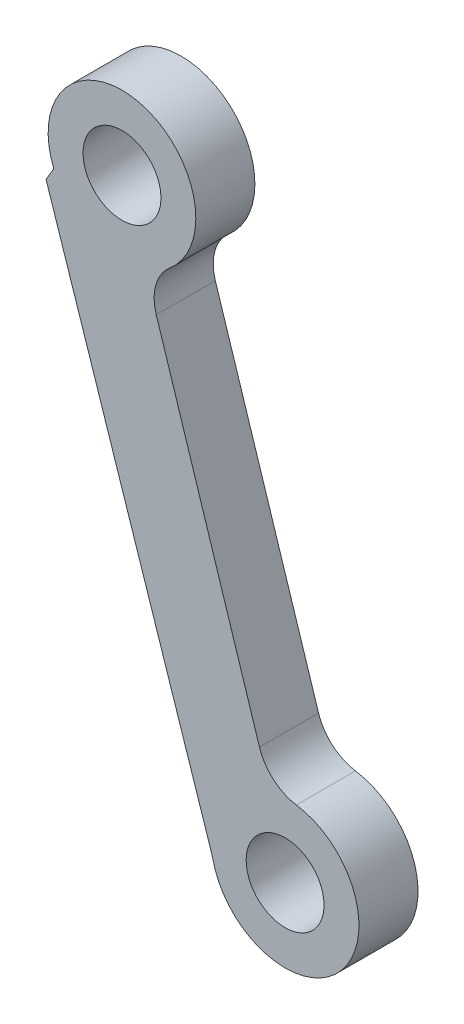
SolidWorks part; units mm, degrees
ref_plane "Front Plane" through (0, 0, 0) normal (0, 0, 1) x (1, 0, 0)
ref_plane "Top Plane" through (0, 0, 0) normal (0, 1, 0) x (1, 0, 0)
ref_plane "Right Plane" through (0, 0, 0) normal (1, 0, 0) x (0, 0, -1)
ref_plane "Plane1" through (0, 0, 4) normal (0, 0, 1) x (1, 0, 0)
sketch "Sketch1" plane through (0, 0, 4) normal (0, 0, 1) x (1, 0, 0)
  line L0 (18.1213, 57.4996) -> (11.1306, 79.363)
  line L1 (4.192, 84.4586) -> (3.6695, 83.5717)
  line L2 (3.6695, 83.5717) -> (14.8419, 49.7795)
  line L3 (14.8419, 49.7795) -> (15.1185, 48.8209)
  circle A0 centre (19.8562, 50.419) radius 2.6375
  arc A1 (15.1185, 48.8209) -> (20.6227, 55.3599) centre (19.8562, 50.419) ccw
  arc A2 (20.6227, 55.3599) -> (18.1213, 57.4996) centre (21.1024, 58.4527) cw
  arc A3 (11.1306, 79.363) -> (12.0464, 82.5636) centre (13.9881, 80.2767) cw
  arc A4 (12.0464, 82.5636) -> (4.192, 84.4586) centre (8.8102, 86.375) ccw
  circle A5 centre (8.8102, 86.375) radius 2.6375
  circle A6 centre (19.8562, 50.419) radius 2.6375 construction
  point P14 (0, 0)
extrude "Boss-Extrude1" add sketch "Sketch1" against normal blind 4
